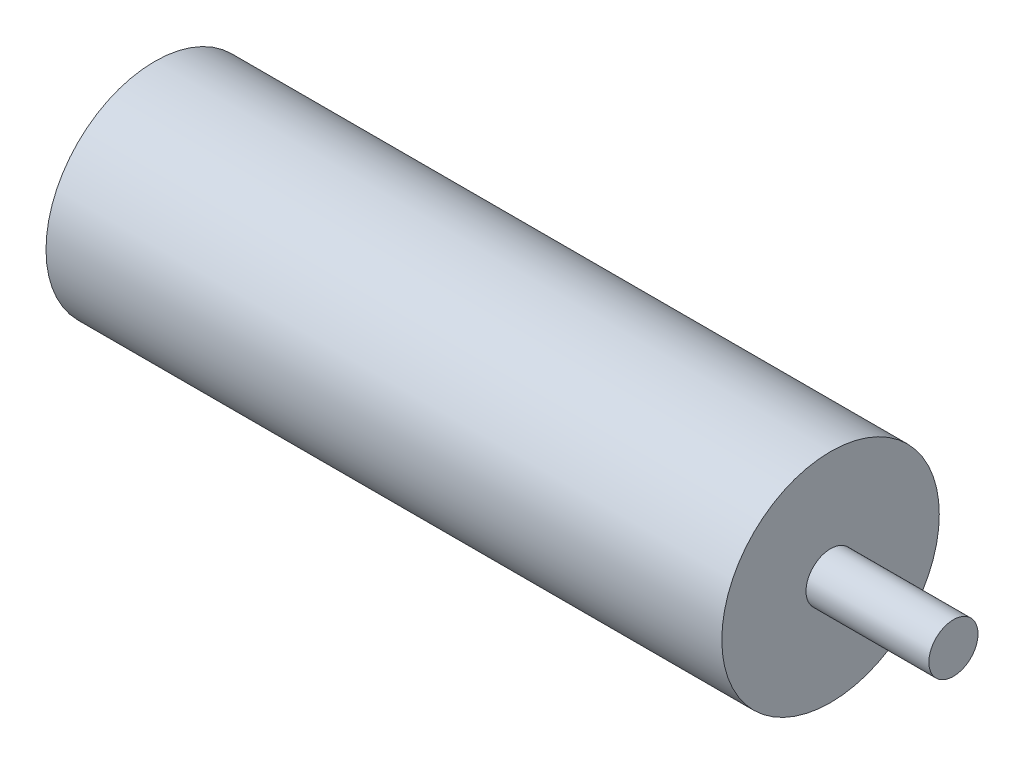
SolidWorks part; units mm, degrees
ref_plane "Front Plane" through (0, 0, 0) normal (0, 0, 1) x (1, 0, 0)
ref_plane "Top Plane" through (0, 0, 0) normal (0, 1, 0) x (1, 0, 0)
ref_plane "Right Plane" through (0, 0, 0) normal (1, 0, 0) x (0, 0, -1)
sketch "Sketch1" plane through (0, 0, 0) normal (1, 0, 0) x (0, 0, -1)
  circle A0 centre (0, 0) radius 22.479
  dimension "D1" = 44.958
extrude "Boss-Extrude1" add sketch "Sketch1" along normal blind 139.7
sketch "Sketch2" plane through (139.7, 0, 0) normal (1, 0, 0) x (0, 0, -1)
  circle A0 centre (0, 0) radius 5.08
  dimension "D1" = 10.16
extrude "Boss-Extrude2" add sketch "Sketch2" along normal blind 25.4
